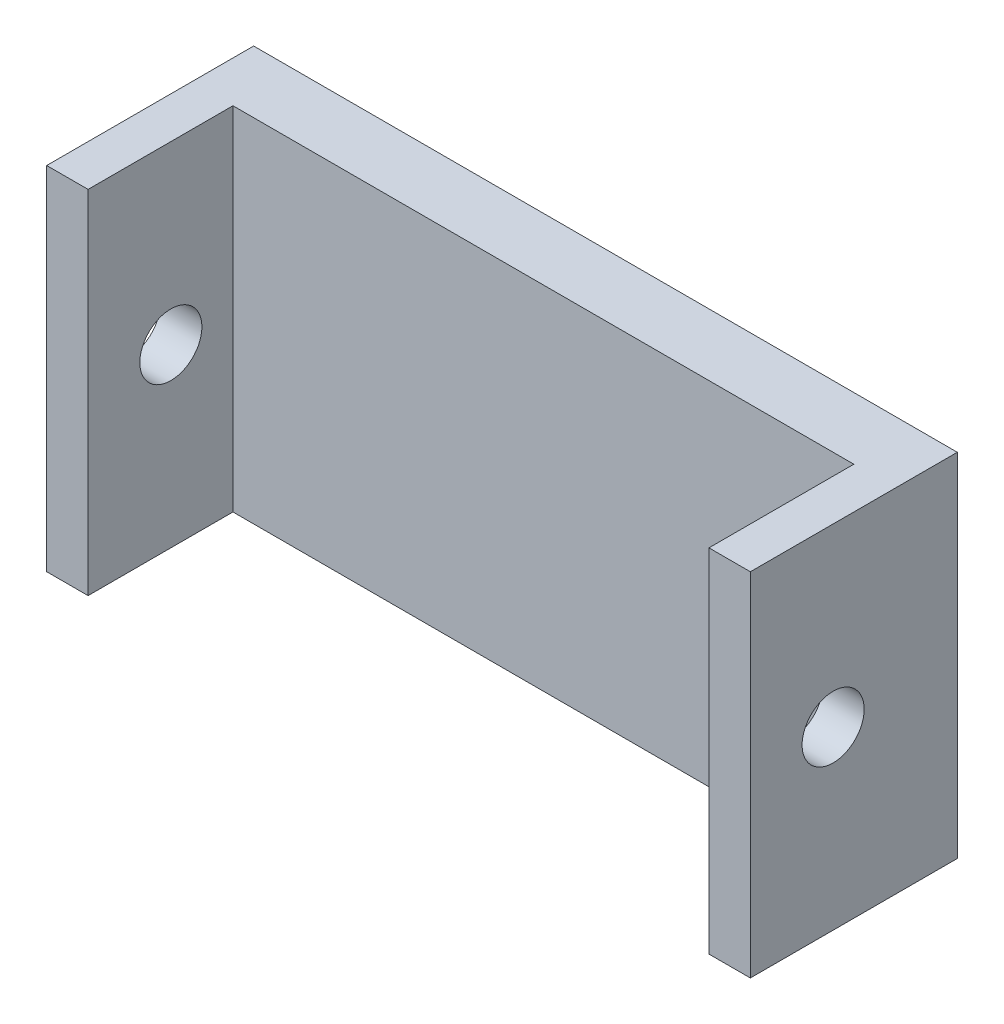
SolidWorks part; units mm, degrees
ref_plane "Plan de face" through (0, 0, 0) normal (0, 0, 1) x (1, 0, 0)
ref_plane "Plan de dessus" through (0, 0, 0) normal (0, 1, 0) x (1, 0, 0)
ref_plane "Plan de droite" through (0, 0, 0) normal (1, 0, 0) x (0, 0, -1)
sketch "Esquisse1" plane through (0, 0, 0) normal (0, 0, 1) x (1, 0, 0)
  line L1 (-15, 8.5) -> (15, 8.5)
  line L2 (-15, 8.5) -> (-15, -8.5)
  line L3 (-15, -8.5) -> (15, -8.5)
  line L4 (15, 8.5) -> (15, -8.5)
  line L5 (-15, 8.5) -> (15, -8.5) construction
  line L6 (-15, -8.5) -> (15, 8.5) construction
  point P0 (0, 0)
  dimension "D1" = 30
  dimension "D2" = 17
extrude "Boss.-Extru.1" add sketch "Esquisse1" along normal blind 3
sketch "Esquisse2" plane through (0, 0, 0) normal (0, 0, 1) x (1, 0, 0)
  line L0 (-15, 8.5) -> (-17, 8.5)
  line L1 (-17, -8.5) -> (-17, 8.5)
  line L2 (-15, -8.5) -> (-17, -8.5)
  line L3 (0, -12.6637) -> (0, 16.7365) construction
  line L4 (-15, 8.5) -> (-15, -8.5) construction
  line L5 (-15, 8.5) -> (-15, -8.5)
  line L6 (15, 8.5) -> (17, 8.5)
  line L7 (17, -8.5) -> (17, 8.5)
  line L8 (15, -8.5) -> (17, -8.5)
  line L9 (15, 8.5) -> (15, -8.5)
  dimension "D1" = 2
extrude "Boss.-Extru.2" add sketch "Esquisse2" along normal blind 10
sketch "Esquisse3" plane through (0, 0, 0) normal (1, 0, 0) x (0, 0, -1)
  line L0 (-3, 8.5) -> (-3, -8.5) construction
  line L2 (-10, -8.5) -> (0, -8.5) construction
  circle A0 centre (-6, 0) radius 1.5
  dimension "D2" = 3
  dimension "D1" = 3
extrude "Enlèv. mat.-Extru.1" cut sketch "Esquisse3" against normal through all both and the other way through all
sketch "Esquisse4" plane through (0, 0, 0) normal (0, 0, -1) x (-1, 0, 0)
  line L0 (-17, -8.5) -> (-17, 8.5) construction
  line L1 (-17, 8.5) -> (17, 8.5) construction
  text T0 "MQ-3 SENSOR"
  dimension "D1" = 0.8
  dimension "D2" = 10
extrude "Enlèv. mat.-Extru.2" cut sketch "Esquisse4" against normal blind 1
